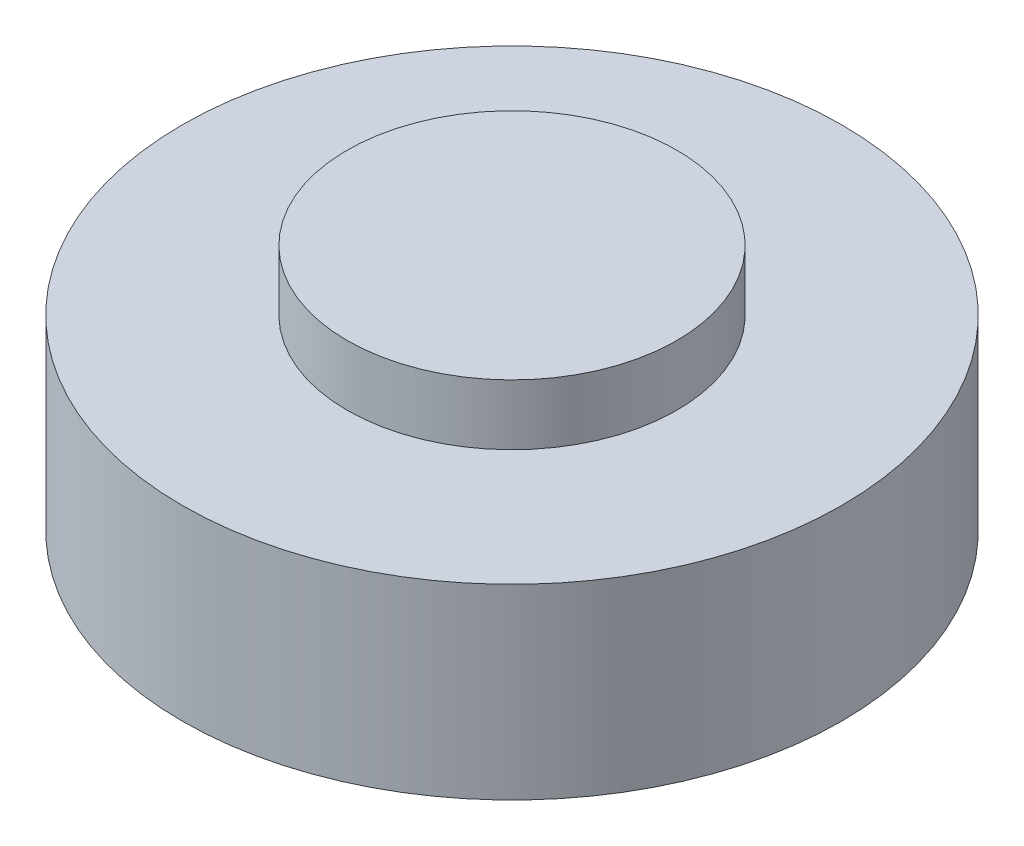
SolidWorks part; units mm, degrees
ref_plane "Alzado" through (0, 0, 0) normal (0, 0, 1) x (1, 0, 0)
ref_plane "Planta" through (0, 0, 0) normal (0, 1, 0) x (1, 0, 0)
ref_plane "Vista lateral" through (0, 0, 0) normal (1, 0, 0) x (0, 0, -1)
sketch "Croquis1" plane through (0, 0, 0) normal (0, 1, 0) x (1, 0, 0)
  circle A0 centre (0, 0) radius 30
  dimension "D1" = 60
extrude "Saliente-Extruir1" add sketch "Croquis1" along normal blind 17
sketch "Croquis2" plane through (0, 17, 0) normal (0, 1, 0) x (1, 0, 0)
  circle A0 centre (0, 0) radius 15
  dimension "D1" = 30
extrude "Saliente-Extruir2" add sketch "Croquis2" along normal blind 5.5
